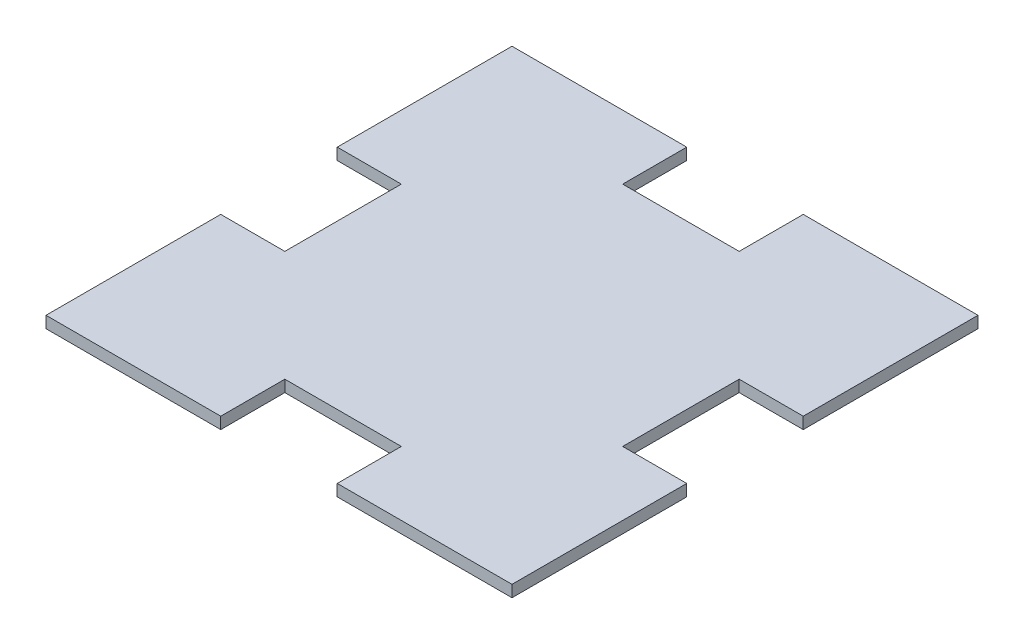
SolidWorks part; units mm, degrees
ref_plane "Front Plane" through (0, 0, 0) normal (0, 0, 1) x (1, 0, 0)
ref_plane "Top Plane" through (0, 0, 0) normal (0, 1, 0) x (1, 0, 0)
ref_plane "Right Plane" through (0, 0, 0) normal (1, 0, 0) x (0, 0, -1)
sketch "Sketch1" plane through (0, 0, 0) normal (0, 1, 0) x (1, 0, 0)
  line L0 (-127, -25.5119) -> (-127, -120.7619)
  line L1 (-127, 133.2381) -> (-31.75, 133.2381)
  line L2 (-127, -25.5119) -> (-92.075, -25.5119)
  line L3 (127, 133.2381) -> (127, 37.9881)
  line L4 (127, -120.7619) -> (31.75, -120.7619)
  line L5 (-92.075, 37.9881) -> (-92.075, -25.5119)
  line L6 (-31.75, 133.2381) -> (-31.75, 98.3131)
  line L7 (-31.75, 98.3131) -> (31.75, 98.3131)
  line L8 (-92.075, 37.9881) -> (-127, 37.9881)
  line L9 (31.75, 98.3131) -> (31.75, 133.2381)
  line L10 (31.75, 133.2381) -> (127, 133.2381)
  line L11 (127, 37.9881) -> (92.075, 37.9881)
  line L12 (92.075, 37.9881) -> (92.075, -25.5119)
  line L13 (-127, 133.2381) -> (-127, 37.9881)
  line L14 (92.075, -25.5119) -> (127, -25.5119)
  line L15 (127, -25.5119) -> (127, -120.7619)
  line L16 (31.75, -120.7619) -> (31.75, -85.8369)
  line L17 (31.75, -85.8369) -> (-31.75, -85.8369)
  line L18 (-31.75, -85.8369) -> (-31.75, -120.7619)
  line L19 (-31.75, -120.7619) -> (-127, -120.7619)
  point P0 (0, 0)
  point P6 (-127, 0)
extrude "Boss-Extrude1" add sketch "Sketch1" along normal blind 6.35
sketch "Sketch2" plane through (-92.075, 0, 0) normal (-1, 0, 0) x (0, 0, 1)
  line L1 (-37.9881, 0) -> (25.5119, 0)
  line L2 (-37.9881, 0) -> (-37.9881, 6.35)
  line L3 (-37.9881, 6.35) -> (25.5119, 6.35)
  line L4 (25.5119, 0) -> (25.5119, 6.35)
